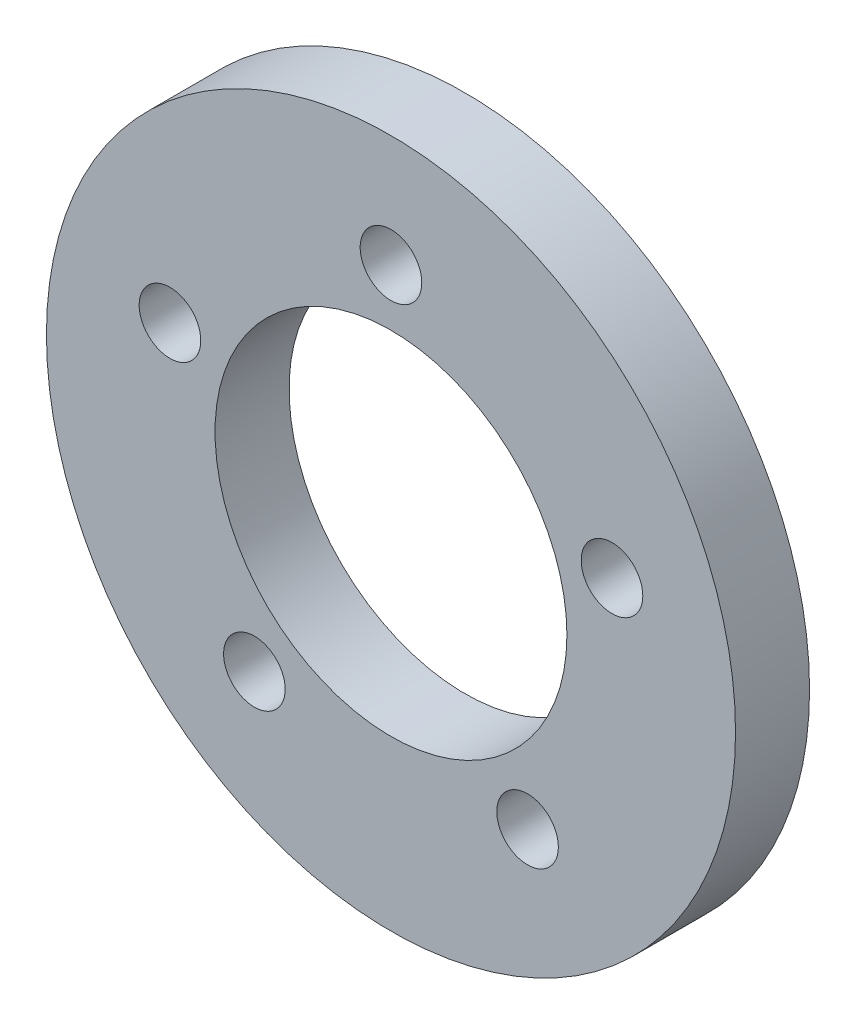
SolidWorks part; units mm, degrees
material "6061 Alloy"
ref_plane "Front Plane" through (0, 0, 0) normal (0, 0, 1) x (1, 0, 0)
ref_plane "Top Plane" through (0, 0, 0) normal (0, 1, 0) x (1, 0, 0)
ref_plane "Right Plane" through (0, 0, 0) normal (1, 0, 0) x (0, 0, -1)
sketch "Sketch1" plane through (0, 0, 0) normal (0, 0, 1) x (1, 0, 0)
  line L0 (0, 15.85) -> (0, 0) construction
  circle A0 centre (0, 0) radius 23.5
  circle A1 centre (0, 0) radius 12
  circle A2 centre (0, 15.85) radius 2.1
  circle A3 centre (0, 0) radius 12
  circle A4 centre (15.0742, 4.8979) radius 2.1
  circle A5 centre (0, 0) radius 12
  circle A6 centre (9.3164, -12.8229) radius 2.1
  circle A7 centre (0, 0) radius 12
  circle A8 centre (-9.3164, -12.8229) radius 2.1
  circle A9 centre (0, 0) radius 12
  circle A10 centre (-15.0742, 4.8979) radius 2.1
  point P20 (0, 0)
  dimension "D1" = 47
  dimension "D2" = 24
  dimension "D3" = 15.85
  dimension "D4" = 4.2
  dimension "D5" = 5
extrude "Boss-Extrude1" add sketch "Sketch1" along normal blind 5.05
